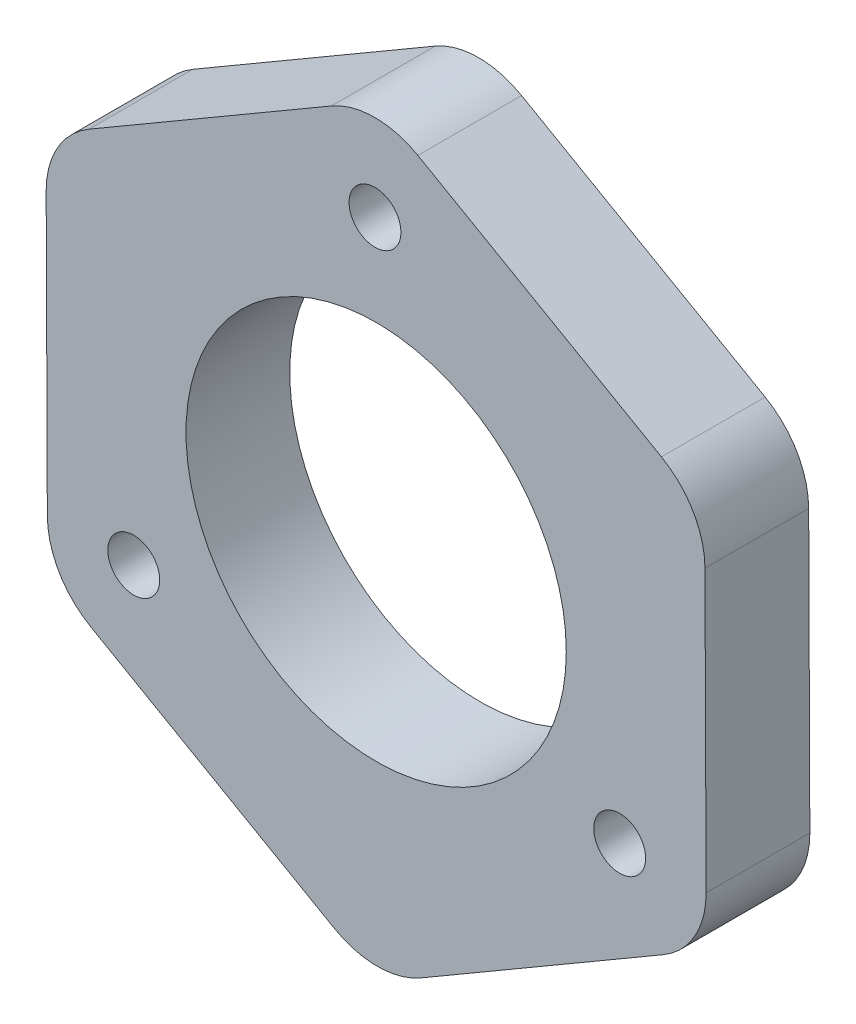
SolidWorks part; units mm, degrees
ref_plane "Front Plane" through (0, 0, 0) normal (0, 0, 1) x (1, 0, 0)
ref_plane "Top Plane" through (0, 0, 0) normal (0, 1, 0) x (1, 0, 0)
ref_plane "Right Plane" through (0, 0, 0) normal (1, 0, 0) x (0, 0, -1)
sketch "Sketch1" plane through (0, 0, 0) normal (0, 0, 1) x (1, 0, 0)
  line L0 (-173.2525, 276.4613) -> (-135.1394, 276.6197) construction
  line L6 (-151.61, 255.99) -> (-137.5882, 264.1633)
  line L7 (-170.7002, 264.0257) -> (-156.611, 255.9692)
  line L8 (-135.1057, 268.5047) -> (-135.1732, 284.7346)
  line L9 (-173.2862, 284.5762) -> (-173.2187, 268.3464)
  line L10 (-137.6917, 289.0552) -> (-151.7809, 297.1118)
  line L11 (-156.7819, 297.091) -> (-170.8037, 288.9176)
  arc A0 (-170.7002, 264.0257) -> (-173.2187, 268.3464) centre (-168.2177, 268.3672) cw
  arc A1 (-156.611, 255.9692) -> (-151.61, 255.99) centre (-154.1285, 260.3106) ccw
  arc A2 (-137.5882, 264.1633) -> (-135.1057, 268.5047) centre (-140.1068, 268.484) ccw
  arc A3 (-135.1732, 284.7346) -> (-137.6917, 289.0552) centre (-140.1742, 284.7138) ccw
  arc A4 (-151.7809, 297.1118) -> (-156.7819, 297.091) centre (-154.2634, 292.7703) ccw
  circle A5 centre (-140.1068, 268.484) radius 1.5
  circle A6 centre (-154.2634, 292.7703) radius 1.5
  circle A7 centre (-168.2177, 268.3672) radius 1.5
  arc A8 (-173.2862, 284.5762) -> (-170.8037, 288.9176) centre (-168.2852, 284.597) cw
  circle A9 centre (-154.196, 276.5405) radius 11
  point P15 (-152.1004, 265.6285)
  dimension "D1" = 3
  dimension "D2" = 38.1133
  dimension "D11" = 5.0011
  dimension "D16" = 22
  dimension "D3" = 16.23
  dimension "D4" = 60
  dimension "D5" = 60
  dimension "D6" = 60
  dimension "D7" = 60
  dimension "D8" = 60
  dimension "D9" = 5.0011
  dimension "D10" = 5.0011
  dimension "D12" = 255.99
  dimension "D13" = 151.61
  dimension "D14" = 297.51
  dimension "D15" = 8.115
extrude "Boss-Extrude1" add sketch "Sketch1" along normal blind 6 separate body
